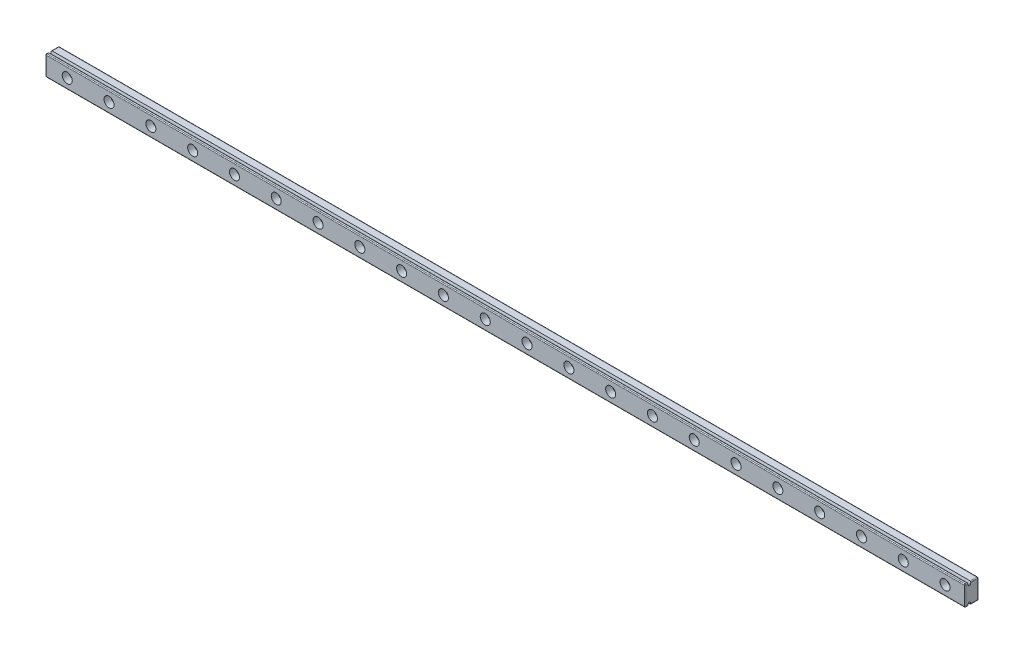
SolidWorks part; units mm, degrees
ref_plane "Front Plane" through (0, 0, 0) normal (0, 0, 1) x (1, 0, 0)
ref_plane "Top Plane" through (0, 0, 0) normal (0, 1, 0) x (1, 0, 0)
ref_plane "Right Plane" through (0, 0, 0) normal (1, 0, 0) x (0, 0, -1)
sketch "Sketch1" plane through (0, 0, 0) normal (1, 0, 0) x (0, 0, -1)
  line L0 (-0.5, 6) -> (4, 6)
  line L1 (-4, 6) -> (-2.5, 6)
  line L2 (-4, 6) -> (-4, -6)
  line L3 (-4, -6) -> (-2.5, -6)
  line L4 (4, 6) -> (4, -6)
  line L5 (-4, 6) -> (4, -6) construction
  line L6 (-4, -6) -> (4, 6) construction
  line L8 (-2.5, 6) -> (-2.5, 4.25)
  line L9 (-2.5, 4.25) -> (-0.5, 4.25)
  line L10 (-0.5, 6) -> (-0.5, 4.25)
  line L12 (-2.5, -6) -> (-2.5, -4.25)
  line L13 (-2.5, -4.25) -> (-0.5, -4.25)
  line L14 (-0.5, -6) -> (-0.5, -4.25)
  line L15 (-0.5, -6) -> (4, -6)
  point P0 (0, 0)
  dimension "D1" = 12
  dimension "D2" = 8
  dimension "D3" = 2
  dimension "D4" = 2
  dimension "D5" = 1.5
  dimension "D6" = 1.5
  dimension "D7" = 8.5
  dimension "D8" = 4.25
extrude "Boss-Extrude1" add sketch "Sketch1" along normal blind 550
sketch "Sketch2" plane through (0, 0, 4) normal (0, 0, 1) x (1, 0, 0)
  line L0 (0, 6) -> (0, -6) construction
  line L1 (0, 0) -> (550, 0) construction
  line L2 (550, 6) -> (550, -6) construction
  circle A0 centre (13, 0) radius 1.75
  circle A1 centre (38, 0) radius 1.75
  circle A2 centre (63, 0) radius 1.75
  circle A3 centre (88, 0) radius 1.75
  circle A4 centre (113, 0) radius 1.75
  circle A5 centre (138, 0) radius 1.75
  circle A6 centre (163, 0) radius 1.75
  circle A7 centre (188, 0) radius 1.75
  circle A8 centre (213, 0) radius 1.75
  circle A9 centre (238, 0) radius 1.75
  circle A10 centre (263, 0) radius 1.75
  circle A11 centre (288, 0) radius 1.75
  circle A12 centre (313, 0) radius 1.75
  circle A13 centre (338, 0) radius 1.75
  circle A14 centre (363, 0) radius 1.75
  circle A15 centre (388, 0) radius 1.75
  circle A16 centre (413, 0) radius 1.75
  circle A17 centre (438, 0) radius 1.75
  circle A18 centre (463, 0) radius 1.75
  circle A19 centre (488, 0) radius 1.75
  circle A21 centre (513, 0) radius 1.75
  circle A22 centre (538, 0) radius 1.75
  dimension "D1" = 3.5
  dimension "D4" = 25
  dimension "D5" = 3.5
  dimension "D6" = 3.5
  dimension "D7" = 3.5
  dimension "D8" = 3.5
  dimension "D10" = 3.5
  dimension "D11" = 3.5
  dimension "D12" = 25
  dimension "D13" = 25
  dimension "D14" = 25
  dimension "D15" = 25
  dimension "D16" = 25
  dimension "D17" = 25
  dimension "D2" = 13
  dimension "D3" = 16
extrude "Cut-Extrude1" cut sketch "Sketch2" against normal blind 10
sketch "Sketch3" plane through (0, 0, 4) normal (0, 0, 1) x (1, 0, 0)
  line L0 (0, 0) -> (550, 0) construction
  line L1 (550, 6) -> (550, -6) construction
  circle A0 centre (13, 0) radius 3
  circle A1 centre (38, 0) radius 3
  circle A2 centre (63, 0) radius 3
  circle A3 centre (88, 0) radius 3
  circle A4 centre (113, 0) radius 3
  circle A5 centre (138, 0) radius 3
  circle A6 centre (163, 0) radius 3
  circle A7 centre (188, 0) radius 3
  circle A8 centre (213, 0) radius 3
  circle A9 centre (238, 0) radius 3
  circle A10 centre (263, 0) radius 3
  circle A11 centre (288, 0) radius 3
  circle A12 centre (313, 0) radius 3
  circle A13 centre (338, 0) radius 3
  circle A14 centre (363, 0) radius 3
  circle A15 centre (388, 0) radius 3
  circle A16 centre (413, 0) radius 3
  circle A17 centre (438, 0) radius 3
  circle A18 centre (463, 0) radius 3
  circle A19 centre (488, 0) radius 3
  circle A20 centre (513, 0) radius 3
  circle A21 centre (538, 0) radius 3
  dimension "D1" = 6
  dimension "D3" = 25
  dimension "D4" = 6
  dimension "D5" = 6
  dimension "D6" = 6
  dimension "D7" = 6
  dimension "D8" = 6
  dimension "D9" = 6
  dimension "D2" = 16
extrude "Cut-Extrude2" cut sketch "Sketch3" against normal blind 4
chamfer "Chamfer1" distance 0.5 angle 74 4 edges at (275, -4.25, 2.5) (275, -4.25, 0.5) (275, 4.25, 2.5) (275, 4.25, 0.5)
fillet "Fillet1" radius 0.5 20 edges at (550, -6, -1.75) (550, 0, -4) (550, 6, -1.75) (550, 6, 3.25) (550, 0, 4) (550, -6, 3.25) (0, -6, 3.25) (0, -6, -1.75) (0, 0, -4) (0, 6, -1.75) (0, 6, 3.25) (0, 0, 4) (275, -4.25, 1) (275, -4.25, 2) (275, 4.25, 2) (275, 4.25, 1) (275, -6, 4) (275, 6, 4) (275, -6, -4) (275, 6, -4)
